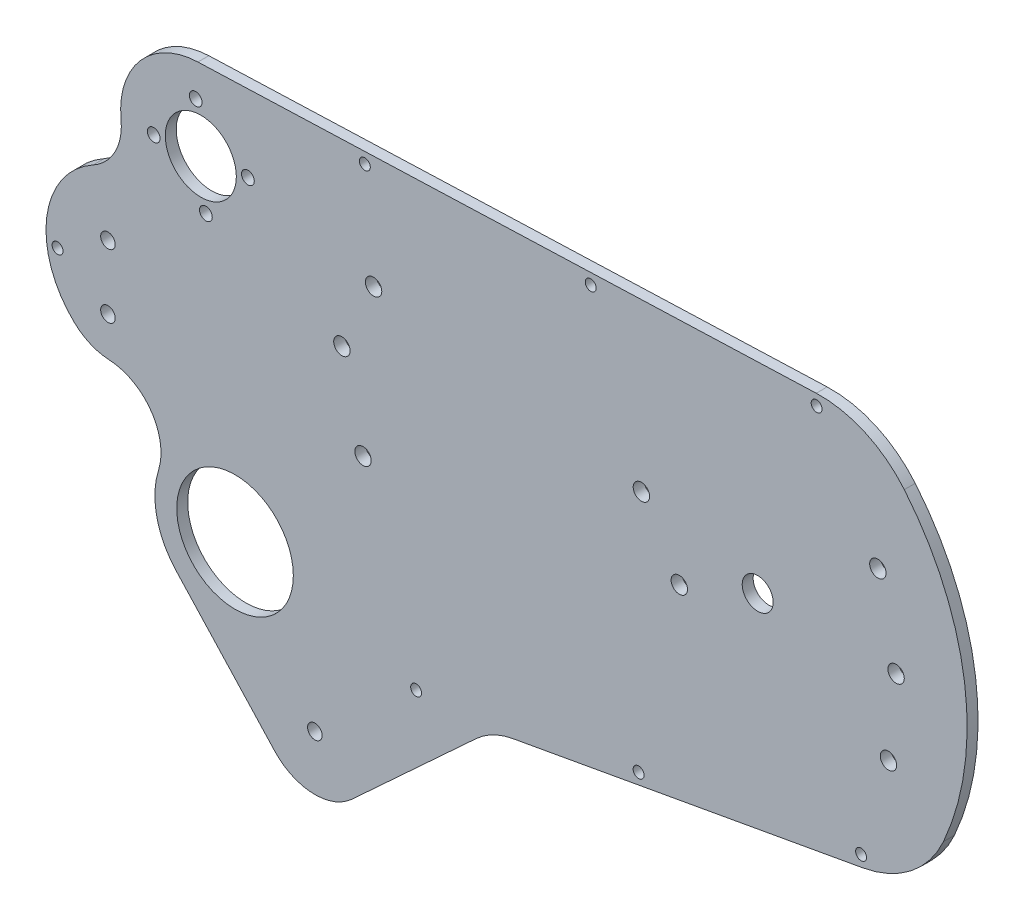
SolidWorks part; units mm, degrees
material "1060 Alloy"
ref_plane "Front Plane" through (0, 0, 0) normal (0, 0, 1) x (1, 0, 0)
ref_plane "Top Plane" through (0, 0, 0) normal (0, 1, 0) x (1, 0, 0)
ref_plane "Right Plane" through (0, 0, 0) normal (1, 0, 0) x (0, 0, -1)
sketch "Sketch1" plane through (0, 0, 0) normal (0, 0, 1) x (1, 0, 0)
  line L0 (86.8854, -33.5) -> (-137.2004, -33.5) construction
  line L1 (-111.886, 49.4802) -> (83.0489, 41.2139) construction
  line L2 (-115.2069, 49.6211) -> (-101.035, -81.6153) construction
  line L3 (-97.8208, -80.7688) -> (92.1699, -30.731) construction
  line L4 (78.7977, 41.3942) -> (86.7407, -32.1609) construction
  line L5 (-108.121, -15.9971) -> (82.7692, 4.6166) construction
  line L6 (91, -33.5) -> (-88.5, -33.5) construction
  line L7 (-97.4673, 5.5) -> (-155.3054, 5.5) construction
  line L8 (-138.3, -14) -> (-155.3054, -14) construction
  line L9 (-138.3, 5.5) -> (-138.3, -33.5) construction
  line L10 (-155.3054, 5.5) -> (-155.3054, -33.5) construction
  line L11 (40.0178, 33.5) -> (40.0178, -33.5) construction
  line L12 (-101.0559, -81.4218) -> (-90.5433, -79.5278)
  line L13 (-91.5, 33.5) -> (88, 33.5) construction
  line L14 (-68.3, -21.5) -> (-107.0746, -25.6872) construction
  line L15 (-138.3, -5.25) -> (-81.5148, -93.5701) construction
  line L17 (-119.5948, -74.4106) -> (-92.5405, -103.7404)
  line L18 (-71.3446, -104.5958) -> (-37.2211, -73.1197)
  line L19 (-27.1401, -68.1042) -> (68.9251, -50.7959)
  line L20 (-117.3596, 49.3503) -> (56.0883, 55.6165)
  circle A0 centre (40.0178, 0) radius 4.25
  circle A1 centre (-112.8181, 27.5) radius 13 construction
  circle A2 centre (-103.4238, -59.4942) radius 13 construction
  arc A3 (-91.5, 33.5) -> (-88.5, -33.5) centre (-18.0922, 3.2198) ccw construction
  circle A4 centre (-68.3, -21.5) radius 2.25
  circle A6 centre (-138.3, -5.25) radius 2
  circle A7 centre (-138.3, -22.75) radius 2
  arc A8 (-142.3827, 10.6321) -> (-147.5429, -29.3643) centre (-130.3054, -11.2571) ccw
  arc A9 (-147.5429, -29.3643) -> (-137.2004, -33.5) centre (-137.2004, -18.5) ccw
  circle A10 centre (-112.8181, 27.5) radius 22
  arc A11 (68.9251, -50.7959) -> (91, -33.5) centre (63.6055, -21.2712) ccw
  circle A12 centre (-103.4238, -59.4942) radius 22
  arc A13 (91, -33.5) -> (80.2612, 44.7896) centre (22.6589, -2.9929) ccw
  arc A14 (91, -33.5) -> (88, 33.5) centre (22.6589, -2.9929) ccw construction
  arc A17 (-124.4228, -52.9336) -> (-137.9704, -33.4802) centre (-138.7403, -48.4604) ccw
  arc A18 (-142.3827, 10.6321) -> (-134.7058, 25.2795) centre (-149.6292, 23.7656) ccw
  circle A19 centre (-74.1, 1.7) radius 2.25
  circle A20 centre (-65.4, 20.2) radius 2.25
  circle A21 centre (8.1, 8.2) radius 2.25
  circle A23 centre (18.5, -8.7) radius 2.25
  circle A25 centre (78, -0.1) radius 2.25
  circle A26 centre (75.9, -21.8) radius 2.25
  circle A27 centre (73, 22.4) radius 2.25
  arc A28 (80.2612, 44.7896) -> (56.0883, 55.6165) centre (57.1714, 25.636) ccw
  circle A30 centre (-81.5148, -93.5701) radius 2
  circle A36 centre (-114.2138, 40.4249) radius 1.75
  circle A37 centre (-99.8933, 28.8957) radius 1.75
  circle A38 centre (-111.4224, 14.5751) radius 1.75
  circle A39 centre (-125.743, 26.1043) radius 1.75
  circle A40 centre (-104.8196, -46.5694) radius 1.75
  circle A41 centre (-90.499, -58.0985) radius 1.75
  circle A42 centre (-102.0281, -72.4191) radius 1.75
  circle A43 centre (-116.3487, -60.89) radius 1.75
  circle A44 centre (40.0178, 0) radius 35 construction
  circle A45 centre (40.0178, 0) radius 43
  circle A49 centre (-103.4238, -59.4942) radius 16
  circle A50 centre (-112.8181, 27.5) radius 16
  circle A51 centre (-112.8181, 27.5) radius 9.75
  circle A52 centre (-103.4238, -59.4942) radius 9.75
  arc A53 (91, -33.5) -> (88, 33.5) centre (22.6589, -2.9929) ccw construction
  arc A54 (-92.5405, -103.7404) -> (-71.3446, -104.5958) centre (-81.5148, -93.5701) ccw
  arc A55 (-27.1401, -68.1042) -> (-37.2211, -73.1197) centre (-23.5699, -87.9191) ccw
  circle A56 centre (-68.3, -21.5) radius 2.25 construction
  circle A57 centre (-74.1, 1.7) radius 2.25 construction
  circle A58 centre (-65.4, 20.2) radius 2.25 construction
  circle A59 centre (18.5, -8.7) radius 2.25 construction
  circle A60 centre (8.1, 8.2) radius 2.25 construction
  circle A61 centre (75.9, -21.8) radius 2.25 construction
  circle A62 centre (78, -0.1) radius 2.25 construction
  circle A63 centre (73, 22.4) radius 2.25 construction
  point P52 (82.7692, 4.6166)
  point P109 (-112.8181, 27.5)
  point P118 (-103.4238, -59.4942)
  dimension "D5" = 4
  dimension "D6" = 25
  dimension "D9" = 15
  dimension "D13" = 30
  dimension "D14" = 26
  dimension "D11" = 44
  dimension "D15" = 3.5
  dimension "D12" = 70
  dimension "D19" = 8.5
  dimension "D20" = 19.5
  dimension "D22" = 32
  dimension "D24" = 4
  dimension "D26" = 55
  dimension "D2" = 39
  dimension "D3" = 70
  dimension "D4" = 17.5
  dimension "D7" = 14
  dimension "D8" = 10
  dimension "D10" = 87.5
  dimension "D21" = 192
  dimension "D23" = 39
  dimension "D25" = 105
  dimension "D18" = 8
  dimension "D16" = 4
  dimension "D17" = 4
extrude "Boss-Extrude1" add sketch "Sketch1" along normal blind 3
sketch "Sketch2" plane through (0, 0, 3) normal (0, 0, 1) x (1, 0, 0)
  line L0 (68.3931, -47.8434) -> (7.3358, -58.8443) construction
  line L1 (-138.3, -5.25) -> (-138.3, -22.75) construction
  line L2 (7.3358, -58.8443) -> (-53.7216, -69.8452) construction
  line L7 (56.1966, 52.6184) -> (-113.5041, 46.4876)
  line L8 (56.1966, 52.6184) -> (-113.5041, 46.4876)
  line L9 (-67.8034, 48.1386) -> (-5.8034, 50.3785) construction
  line L10 (-5.8034, 50.3785) -> (56.1966, 52.6184) construction
  line L13 (-117.3897, -72.3766) -> (-90.3354, -101.7064)
  line L14 (-73.3786, -102.3907) -> (-39.2552, -70.9146)
  line L15 (-27.672, -65.1517) -> (68.3931, -47.8434)
  line L17 (-117.3897, -72.3766) -> (-90.3354, -101.7064) construction
  line L18 (-73.3786, -102.3907) -> (-39.2552, -70.9146) construction
  line L19 (-110.3186, -80.0424) -> (68.3931, -47.8434) construction
  circle A0 centre (7.3358, -58.8443) radius 1.5
  circle A2 centre (-53.7216, -69.8452) radius 1.5
  arc A14 (77.9522, 42.8742) -> (56.1966, 52.6184) centre (57.1714, 25.636) ccw
  arc A15 (77.9522, 42.8742) -> (56.1966, 52.6184) centre (57.1714, 25.636) ccw
  arc A16 (68.3931, -47.8434) -> (88.2606, -32.2771) centre (63.6055, -21.2712) ccw
  arc A17 (-114.7845, -75.2008) -> (-103.8362, -78.8745) centre (-105.964, -67.0646) ccw construction
  circle A21 centre (68.3931, -47.8434) radius 1.5
  circle A23 centre (56.1966, 52.6184) radius 1.5
  circle A24 centre (-5.8034, 50.3785) radius 1.5
  circle A27 centre (-67.8034, 48.1386) radius 1.5
  arc A28 (-113.5041, 46.4876) -> (-131.7211, 25.5823) centre (-112.8181, 27.5) ccw
  arc A29 (-140.9335, 8.0053) -> (-131.7211, 25.5823) centre (-149.6292, 23.7656) ccw
  arc A30 (-140.9335, 8.0053) -> (-145.4744, -27.1914) centre (-130.3054, -11.2571) ccw
  arc A31 (-145.4744, -27.1914) -> (-137.8164, -30.4842) centre (-137.2004, -18.5) ccw
  arc A32 (-121.5593, -53.8282) -> (-137.8164, -30.4842) centre (-138.7403, -48.4604) ccw
  arc A33 (-121.5593, -53.8282) -> (-117.3897, -72.3766) centre (-103.4238, -59.4942) ccw
  arc A34 (-90.3354, -101.7064) -> (-73.3786, -102.3907) centre (-81.5148, -93.5701) ccw
  arc A35 (-27.672, -65.1517) -> (-39.2552, -70.9146) centre (-23.5699, -87.9191) ccw
  arc A36 (88.2606, -32.2771) -> (77.9522, 42.8742) centre (22.6589, -2.9929) ccw
  arc A37 (-113.5041, 46.4876) -> (-131.7211, 25.5823) centre (-112.8181, 27.5) ccw construction
  arc A38 (-140.9335, 8.0053) -> (-131.7211, 25.5823) centre (-149.6292, 23.7656) ccw construction
  arc A39 (-140.9335, 8.0053) -> (-145.4744, -27.1914) centre (-130.3054, -11.2571) ccw construction
  arc A40 (-145.4744, -27.1914) -> (-137.8164, -30.4842) centre (-137.2004, -18.5) ccw construction
  arc A41 (-121.5593, -53.8282) -> (-137.8164, -30.4842) centre (-138.7403, -48.4604) ccw construction
  arc A42 (-121.5593, -53.8282) -> (-117.3897, -72.3766) centre (-103.4238, -59.4942) ccw construction
  arc A43 (-90.3354, -101.7064) -> (-73.3786, -102.3907) centre (-81.5148, -93.5701) ccw construction
  arc A44 (-27.672, -65.1517) -> (-39.2552, -70.9146) centre (-23.5699, -87.9191) ccw construction
  arc A45 (88.2606, -32.2771) -> (77.9522, 42.8742) centre (22.6589, -2.9929) ccw construction
  circle A47 centre (-152.1337, -14) radius 1.5
  arc A51 (68.3931, -47.8434) -> (88.2606, -32.2771) centre (63.6055, -21.2712) ccw
  point P2 (-138.3, -14)
  dimension "D4" = 3
  dimension "D2" = 62
  dimension "D1" = 3
extrude "Cut-Extrude1" cut sketch "Sketch2" against normal through all
